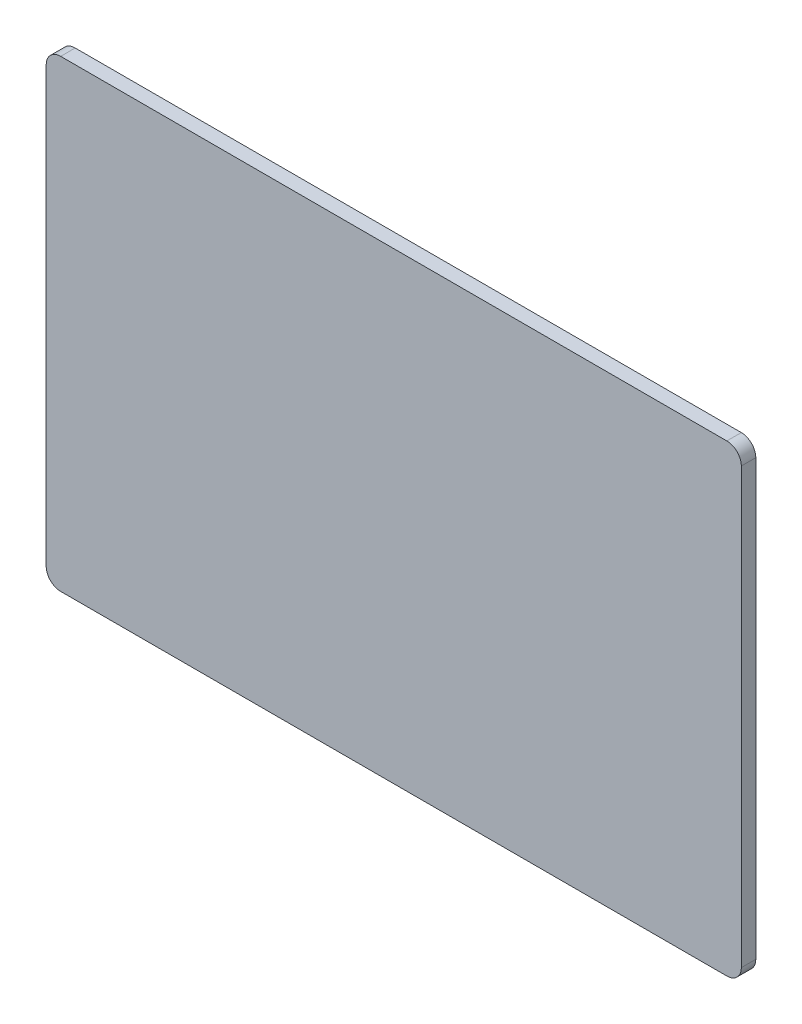
SolidWorks part; units mm, degrees
ref_plane "Front Plane" through (0, 0, 0) normal (0, 0, 1) x (1, 0, 0)
ref_plane "Top Plane" through (0, 0, 0) normal (0, 1, 0) x (1, 0, 0)
ref_plane "Right Plane" through (0, 0, 0) normal (1, 0, 0) x (0, 0, -1)
sketch "Sketch1" plane through (0, 0, 0) normal (0, 0, 1) x (1, 0, 0)
  line L1 (0, 0) -> (76.2, 0)
  line L2 (0, 0) -> (0, 50.8)
  line L3 (0, 50.8) -> (76.2, 50.8)
  line L4 (76.2, 0) -> (76.2, 50.8)
  dimension "D1" = 76.2
  dimension "D2" = 50.8
extrude "Boss-Extrude1" add sketch "Sketch1" along normal blind 1.5875
fillet "Fillet1" radius 1.5875 4 edges at (0, 0, 0.7937) (0, 50.8, 0.7937) (76.2, 0, 0.7937) (76.2, 50.8, 0.7937)
sketch "Sketch2" plane through (0, 0, 1.5875) normal (0, 0, 1) x (1, 0, 0)
  text T0 "<i>Cherry Lady</i>" font "Vladimir Script" height in points 36
sketch "Sketch3" plane through (0, 0, 1.5875) normal (0, 0, 1) x (1, 0, 0)
  text T0 "Designed by:\r\nNicholas Grummon Apr 2026"
